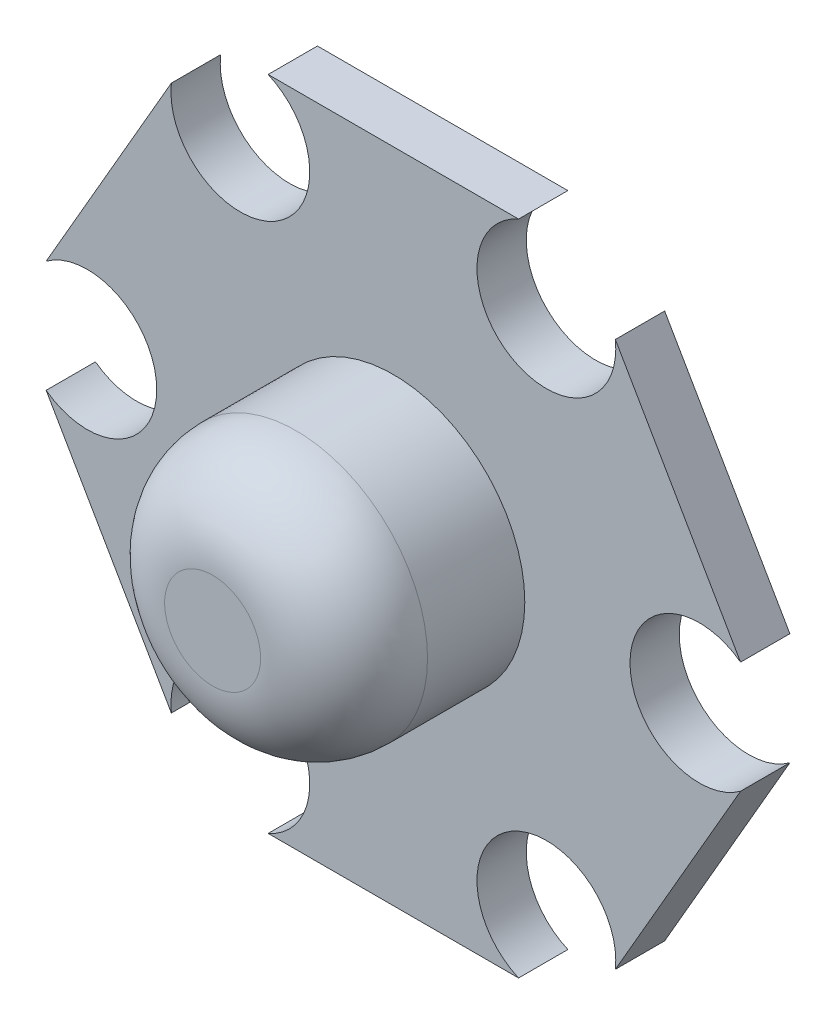
SolidWorks part; units mm, degrees
material "6061-T6 (SS)"
ref_plane "Front Plane" through (0, 0, 0) normal (0, 0, 1) x (1, 0, 0)
ref_plane "Top Plane" through (0, 0, 0) normal (0, 1, 0) x (1, 0, 0)
ref_plane "Right Plane" through (0, 0, 0) normal (1, 0, 0) x (0, 0, -1)
sketch "Sketch1" plane through (0, 0, 0) normal (0, 0, 1) x (1, 0, 0)
  line L0 (-3.81, 10) -> (3.81, 10)
  line L1 (6.7553, 8.2996) -> (10.5653, 1.7004)
  line L2 (10.5653, -1.7004) -> (6.7553, -8.2996)
  line L3 (3.81, -10) -> (-3.81, -10)
  line L4 (-6.7553, -8.2996) -> (-10.5653, -1.7004)
  line L5 (-10.5653, 1.7004) -> (-6.7553, 8.2996)
  arc A0 (-6.7553, 8.2996) -> (-3.81, 10) centre (-4.6561, 8.0646) ccw
  circle A1 centre (0, 0) radius 4 construction
  circle A2 centre (0, 0) radius 7.2 construction
  arc A3 (3.81, 10) -> (6.7553, 8.2996) centre (4.6561, 8.0646) ccw
  arc A4 (10.5653, 1.7004) -> (10.5653, -1.7004) centre (9.3122, 0) ccw
  arc A5 (6.7553, -8.2996) -> (3.81, -10) centre (4.6561, -8.0646) ccw
  arc A6 (-3.81, -10) -> (-6.7553, -8.2996) centre (-4.6561, -8.0646) ccw
  arc A7 (-10.5653, -1.7004) -> (-10.5653, 1.7004) centre (-9.3122, 0) ccw
  point P5 (0, 10)
  point P20 (0, 0)
  point P37 (0, 0)
  dimension "D1" = 8
  dimension "D3" = 14.4
  dimension "D6" = 2.1122
  dimension "D2" = 10
  dimension "D4" = 7.62
  dimension "D5" = 6
  dimension "D7" = 6
extrude "Boss-Extrude1" add sketch "Sketch1" along normal blind 1.5
sketch "Sketch2" plane through (0, 0, 1.5) normal (0, 0, 1) x (1, 0, 0)
  circle A0 centre (0, 0) radius 4
  dimension "D1" = 8
extrude "Boss-Extrude2" add sketch "Sketch2" along normal blind 5.5
fillet "Fillet1" radius 2.54 1 edges at (4, 0, 7)
sketch "Sketch3" plane through (0, 0, 1.5) normal (0, 0, 1) x (1, 0, 0)
  line L0 (-17.3205, 10) -> (-17.3205, 20) construction
  line L1 (-17.3205, 10) -> (-8.6603, 5) construction
  line L2 (-17.3205, 10) -> (-25.9808, 5) construction
  line L3 (-6.7553, 8.2996) -> (-10.5653, 1.7004) construction
  circle A0 centre (-17.3205, 10) radius 10 construction
  circle A1 centre (-17.3205, 10) radius 30 construction
  dimension "D1" = 20
  dimension "D2" = 60
  dimension "D3" = 120
  dimension "D4" = 120
